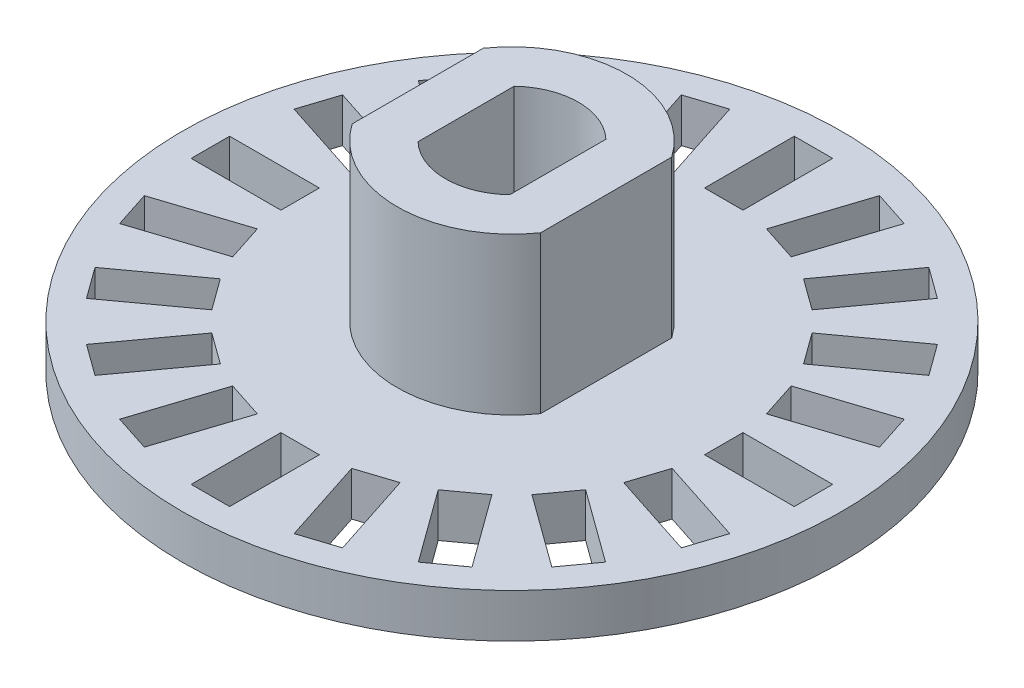
SolidWorks part; units mm, degrees
ref_plane "Plano frontal" through (0, 0, 0) normal (0, 0, 1) x (1, 0, 0)
ref_plane "Plano superior" through (0, 0, 0) normal (0, 1, 0) x (1, 0, 0)
ref_plane "Plano direito" through (0, 0, 0) normal (1, 0, 0) x (0, 0, -1)
sketch "Esboço1" plane through (0, 0, 0) normal (0, 1, 0) x (1, 0, 0)
  line L0 (0, 0) -> (-4.75, 0)
  line L1 (-4.75, 0) -> (4.75, 0)
  line L2 (4.75, 0) -> (0, 0)
  line L3 (-3.9, 0) -> (0, 0)
  line L4 (3.9, 0) -> (0, 0)
  line L5 (-3.9, 0) -> (-3.9, 2.7115)
  line L6 (-3.9, 2.7115) -> (-3.9, -2.7115)
  line L7 (3.9, 2.7115) -> (3.9, -2.7115)
  line L8 (3.9, -2.7115) -> (3.9, 2.7115)
  circle A0 centre (0, 0) radius 4.75
  dimension "D1" = 9.5
  dimension "D2" = 3.9
  dimension "D3" = 3.9
extrude "Extrusão1" add sketch "Esboço1" along normal blind 8.3 contours L6 A0 L7 L1 L0 | L7 A0 L5 L0 L1
sketch "Esboço2" plane through (0, 8.3, 0) normal (0, 1, 0) x (1, 0, 0)
  line L0 (0, 0) -> (-2.75, 0)
  line L1 (-2.75, 0) -> (2.75, 0)
  line L2 (2.75, 0) -> (0, 0)
  line L3 (-1.9, 0) -> (0, 0)
  line L4 (1.9, 0) -> (0, 0)
  line L5 (-1.9, 0) -> (-1.9, 1.9881)
  line L6 (-1.9, 1.9881) -> (-1.9, -1.9881)
  line L7 (-1.9, -1.9881) -> (-1.9, 0)
  line L8 (1.9, 0) -> (1.9, -1.9881)
  line L9 (1.9, -1.9881) -> (1.9, 1.9881)
  line L10 (1.9, 1.9881) -> (1.9, 0)
  circle A0 centre (0, 0) radius 2.75
  dimension "D1" = 5.5
  dimension "D2" = 1.9
  dimension "D3" = 1.9
extrude "Extrusão2" cut sketch "Esboço2" against normal blind 7.3 contours L9 A0 L5 L0 L1 | L6 A0 L8 L1 L0
scale "Escala3" bodies to scale 102 scale about origin uniform scaling yes scale factor 1.1
sketch "Esboço3" plane through (0, 0, 0) normal (0, 1, 0) x (1, 0, 0)
  circle A0 centre (0, 0) radius 15
extrude "Extrusão3" add sketch "Esboço3" along normal blind 2
sketch "Esboço4" plane through (0, 2, 0) normal (0, 1, 0) x (1, 0, 0)
  line L0 (-2.09, 0) -> (-2.09, 2.1869)
  line L1 (-2.09, -2.1869) -> (-2.09, 2.1869) construction
  line L2 (-2.09, 2.1869) -> (-2.09, -2.1869)
  line L3 (2.09, 0) -> (2.09, 2.1869)
  line L4 (2.09, 2.1869) -> (2.09, -2.1869) construction
  line L5 (2.09, 2.1869) -> (2.09, -2.1869)
  arc A0 (-2.09, -2.1869) -> (2.09, -2.1869) centre (0, 0) ccw
  arc A1 (2.09, 2.1869) -> (-2.09, 2.1869) centre (0, 0) ccw
  line M1 (2.09, -2.1869) -> (2.09, 2.1869)
  arc M2 (2.09, 2.1869) -> (-2.09, 2.1869) centre (0, 0) ccw
  line M3 (-2.09, 2.1869) -> (-2.09, -2.1869)
  arc M4 (-2.09, -2.1869) -> (2.09, -2.1869) centre (0, 0) ccw
extrude "Extrusão4" cut sketch "Esboço4" against normal through all contours M1 M2 M3 M4
sketch "Esboço5" plane through (0, 0, 0) normal (0, -1, 0) x (1, 0, 0)
  line L0 (0, 0) -> (0, -15)
  line L1 (0, -15) -> (0, 0)
  line L2 (-3.8111, -8.8986) -> (-2.1472, -9.4392)
  line L3 (-0.8747, -9.6407) -> (0.8747, -9.6407)
  line L4 (-0.8747, -9.6407) -> (-0.8747, -13.7241)
  line L5 (-0.8747, -13.7241) -> (0.8747, -13.7241)
  line L6 (0.8747, -9.6407) -> (0.8747, -13.7241)
  line L7 (-0.8747, -9.6407) -> (0.8747, -13.7241) construction
  line L8 (-0.8747, -13.7241) -> (0.8747, -9.6407) construction
  line L9 (-3.8111, -8.8986) -> (-5.0729, -12.7821)
  line L10 (-5.0729, -12.7821) -> (-3.4091, -13.3227)
  line L11 (-2.1472, -9.4392) -> (-3.4091, -13.3227)
  line L12 (-6.3744, -7.2854) -> (-4.959, -8.3137)
  line L13 (-6.3744, -7.2854) -> (-8.7745, -10.5889)
  line L14 (-8.7745, -10.5889) -> (-7.3592, -11.6172)
  line L15 (-4.959, -8.3137) -> (-7.3592, -11.6172)
  line L16 (-8.3137, -4.959) -> (-7.2854, -6.3744)
  line L17 (-8.3137, -4.959) -> (-11.6172, -7.3592)
  line L18 (-11.6172, -7.3592) -> (-10.5889, -8.7745)
  line L19 (-7.2854, -6.3744) -> (-10.5889, -8.7745)
  line L20 (-9.4392, -2.1472) -> (-8.8986, -3.8111)
  line L21 (-9.4392, -2.1472) -> (-13.3227, -3.4091)
  line L22 (-13.3227, -3.4091) -> (-12.7821, -5.0729)
  line L23 (-8.8986, -3.8111) -> (-12.7821, -5.0729)
  line L24 (-9.6407, 0.8747) -> (-9.6407, -0.8747)
  line L25 (-9.6407, 0.8747) -> (-13.7241, 0.8747)
  line L26 (-13.7241, 0.8747) -> (-13.7241, -0.8747)
  line L27 (-9.6407, -0.8747) -> (-13.7241, -0.8747)
  line L28 (-8.8986, 3.8111) -> (-9.4392, 2.1472)
  line L29 (-8.8986, 3.8111) -> (-12.7821, 5.0729)
  line L30 (-12.7821, 5.0729) -> (-13.3227, 3.4091)
  line L31 (-9.4392, 2.1472) -> (-13.3227, 3.4091)
  line L32 (-7.2854, 6.3744) -> (-8.3137, 4.959)
  line L33 (-7.2854, 6.3744) -> (-10.5889, 8.7745)
  line L34 (-10.5889, 8.7745) -> (-11.6172, 7.3592)
  line L35 (-8.3137, 4.959) -> (-11.6172, 7.3592)
  line L36 (-4.959, 8.3137) -> (-6.3744, 7.2854)
  line L37 (-4.959, 8.3137) -> (-7.3592, 11.6172)
  line L38 (-7.3592, 11.6172) -> (-8.7745, 10.5889)
  line L39 (-6.3744, 7.2854) -> (-8.7745, 10.5889)
  line L40 (-2.1472, 9.4392) -> (-3.8111, 8.8986)
  line L41 (-2.1472, 9.4392) -> (-3.4091, 13.3227)
  line L42 (-3.4091, 13.3227) -> (-5.0729, 12.7821)
  line L43 (-3.8111, 8.8986) -> (-5.0729, 12.7821)
  line L44 (0.8747, 9.6407) -> (-0.8747, 9.6407)
  line L45 (0.8747, 9.6407) -> (0.8747, 13.7241)
  line L46 (0.8747, 13.7241) -> (-0.8747, 13.7241)
  line L47 (-0.8747, 9.6407) -> (-0.8747, 13.7241)
  line L48 (3.8111, 8.8986) -> (2.1472, 9.4392)
  line L49 (3.8111, 8.8986) -> (5.0729, 12.7821)
  line L50 (5.0729, 12.7821) -> (3.4091, 13.3227)
  line L51 (2.1472, 9.4392) -> (3.4091, 13.3227)
  line L52 (6.3744, 7.2854) -> (4.959, 8.3137)
  line L53 (6.3744, 7.2854) -> (8.7745, 10.5889)
  line L54 (8.7745, 10.5889) -> (7.3592, 11.6172)
  line L55 (4.959, 8.3137) -> (7.3592, 11.6172)
  line L56 (8.3137, 4.959) -> (7.2854, 6.3744)
  line L57 (8.3137, 4.959) -> (11.6172, 7.3592)
  line L58 (11.6172, 7.3592) -> (10.5889, 8.7745)
  line L59 (7.2854, 6.3744) -> (10.5889, 8.7745)
  line L60 (9.4392, 2.1472) -> (8.8986, 3.8111)
  line L61 (9.4392, 2.1472) -> (13.3227, 3.4091)
  line L62 (13.3227, 3.4091) -> (12.7821, 5.0729)
  line L63 (8.8986, 3.8111) -> (12.7821, 5.0729)
  line L64 (9.6407, -0.8747) -> (9.6407, 0.8747)
  line L65 (9.6407, -0.8747) -> (13.7241, -0.8747)
  line L66 (13.7241, -0.8747) -> (13.7241, 0.8747)
  line L67 (9.6407, 0.8747) -> (13.7241, 0.8747)
  line L68 (8.8986, -3.8111) -> (9.4392, -2.1472)
  line L69 (8.8986, -3.8111) -> (12.7821, -5.0729)
  line L70 (12.7821, -5.0729) -> (13.3227, -3.4091)
  line L71 (9.4392, -2.1472) -> (13.3227, -3.4091)
  line L72 (7.2854, -6.3744) -> (8.3137, -4.959)
  line L73 (7.2854, -6.3744) -> (10.5889, -8.7745)
  line L74 (10.5889, -8.7745) -> (11.6172, -7.3592)
  line L75 (8.3137, -4.959) -> (11.6172, -7.3592)
  line L76 (4.959, -8.3137) -> (6.3744, -7.2854)
  line L77 (4.959, -8.3137) -> (7.3592, -11.6172)
  line L78 (7.3592, -11.6172) -> (8.7745, -10.5889)
  line L79 (6.3744, -7.2854) -> (8.7745, -10.5889)
  line L80 (2.1472, -9.4392) -> (3.8111, -8.8986)
  line L81 (2.1472, -9.4392) -> (3.4091, -13.3227)
  line L82 (3.4091, -13.3227) -> (5.0729, -12.7821)
  line L83 (3.8111, -8.8986) -> (5.0729, -12.7821)
  circle A0 centre (0, 0) radius 15 construction
  point P6 (0, -11.6824)
extrude "Extrusão5" cut sketch "Esboço5" against normal blind 2 contours L11 L2 L9 L10 | L15 L12 L13 L14 | L19 L16 L17 L18 | L83 L80 L81 L82 | L79 L76 L77 L78 | L75 L72 L73 L74 | L71 L68 L69 L70 | L67 L64 L65 L66 | L63 L60 L61 L62 | L55 L52 L53 L54 | L47 L44 L45 L46 | L43 L40 L41 L42 | L27 L24 L25 L26 | L23 L22 L21 L20 | L3 L6 L5 L4 | L56 L59 L58 L57 | L51 L50 L49 L48 | L38 L39 L36 L37 | L34 L35 L32 L33 | L30 L31 L28 L29
